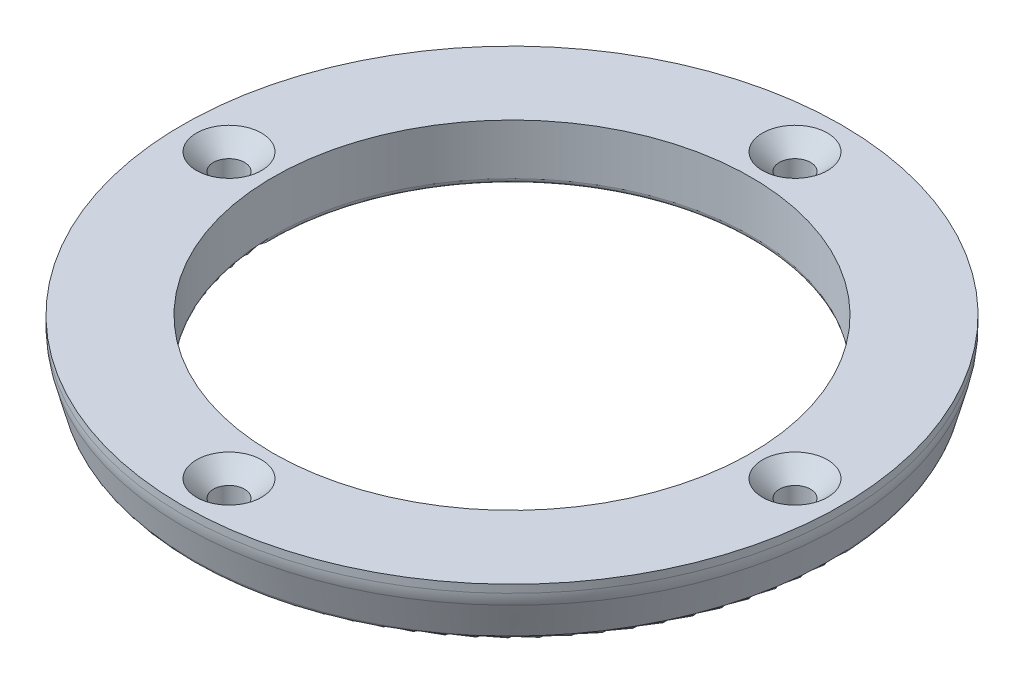
SolidWorks part; units mm, degrees
ref_plane "Front Plane" through (0, 0, 0) normal (0, 0, 1) x (1, 0, 0)
ref_plane "Top Plane" through (0, 0, 0) normal (0, 1, 0) x (1, 0, 0)
ref_plane "Right Plane" through (0, 0, 0) normal (1, 0, 0) x (0, 0, -1)
sketch "Sketch1" plane through (0, 0, 0) normal (0, 1, 0) x (1, 0, 0)
  circle A0 centre (0, 0) radius 59.944 construction
  circle A1 centre (0, 0) radius 47.244
  circle A2 centre (0, 0) radius 34.544
  dimension "D1" = 119.888
  dimension "D2" = 12.7
  dimension "D3" = 12.7
extrude "Boss-Extrude1" add sketch "Sketch1" along normal blind 8.128
sketch "Sketch2" plane through (0, 8.128, 0) normal (0, 1, 0) x (1, 0, 0)
  line L0 (0, 0) -> (0, 34.544) construction
  line L1 (0, 34.544) -> (0, 47.244) construction
  circle A2 centre (0, 0) radius 34.544 construction
  circle A3 centre (0, 0) radius 47.244 construction
  point P3 (0, 40.894)
hole_wizard "CSK for M4 Flat Head Machine Screw1" positions "3DSketch1" profile "Sketch3" countersink size "M4" standard "ANSI Metric" end condition through all
sketch3d "3DSketch1"
  point P0 (0, 8.128, -40.894)
sketch "Sketch3" plane through (0, 8.128, -40.894) normal (1, 0, 0) x (0, 0, 1)
  line L0 (0, 0) -> (0, 8.128)
  line L1 (0, 8.128) -> (2.25, 8.128)
  line L2 (2.25, 8.128) -> (2.25, 2.45)
  line L3 (2.25, 2.45) -> (4.7, 0)
  line L5 (4.7, 0) -> (0, 0)
  line L6 (-2.25, 2.45) -> (-4.7, 0) construction
  line L11 (0, -6.35) -> (0, 107.95) construction
  dimension "Thru Hole Dia." = 4.5
  dimension "Thru Hole Depth" = 8.128
  dimension "Near C'Sink Dia." = 9.4
  dimension "Near C'Sink Angle" = 90
pattern_circular "CirPattern1" count 4 over 360 about axis through (0, 0, 0) along (0, 1, 0) of "CSK for M4 Flat Head Machine Screw1"
draft "Draft1" [suppressed] type of draft neutral plane draft angle 3 faces to draft 1 parameters "D1"=3
draft "Draft2" type of draft neutral plane draft angle 15 faces to draft 1 face at (0, 8.128, 47.244) neutral plane through (0, 0, 0) neutral plane normal (0, -1, 0) parameters "D1"=15
sketch "Sketch5" plane through (0, 0, 0) normal (1, 0, 0) x (0, 0, -1)
  line L1 (48.1519, 8.128) -> (49.4219, 8.128)
  line L2 (34.544, 8.128) -> (47.244, 8.128) construction
  line L3 (49.4219, 8.128) -> (-49.4219, 8.128) construction
  line L4 (49.4219, 8.128) -> (47.244, 0)
  line L5 (47.244, 0) -> (45.974, 0)
  line L6 (-47.244, 0) -> (47.244, 0) construction
  line L7 (45.974, 0) -> (48.1519, 8.128)
  dimension "D1" = 1.27
ref_axis "Axis1" through (0, 8.128, 0) along (0, -1, 0)
revolve "Cut-Revolve1" cut sketch "Sketch5" angle 360 about axis through (0, 8.128, 0) along (0, -1, 0)
sketch "Sketch6" plane through (0, 8.128, 0) normal (0, 1, 0) x (1, 0, 0)
  circle A2 centre (0, 0) radius 47.6227
  circle A3 centre (0, 0) radius 47.6227
  dimension "D1" = 0.5292
extrude "Cut-Extrude1" cut sketch "Sketch6" against normal through all flip side to cut
fillet "Fillet1" radius 6.35 1 edges at (0, 6.1531, 47.6227)
fillet "Fillet2" radius 0.7937 2 edges at (0, 0, 45.974) (0, 0, 34.544)
